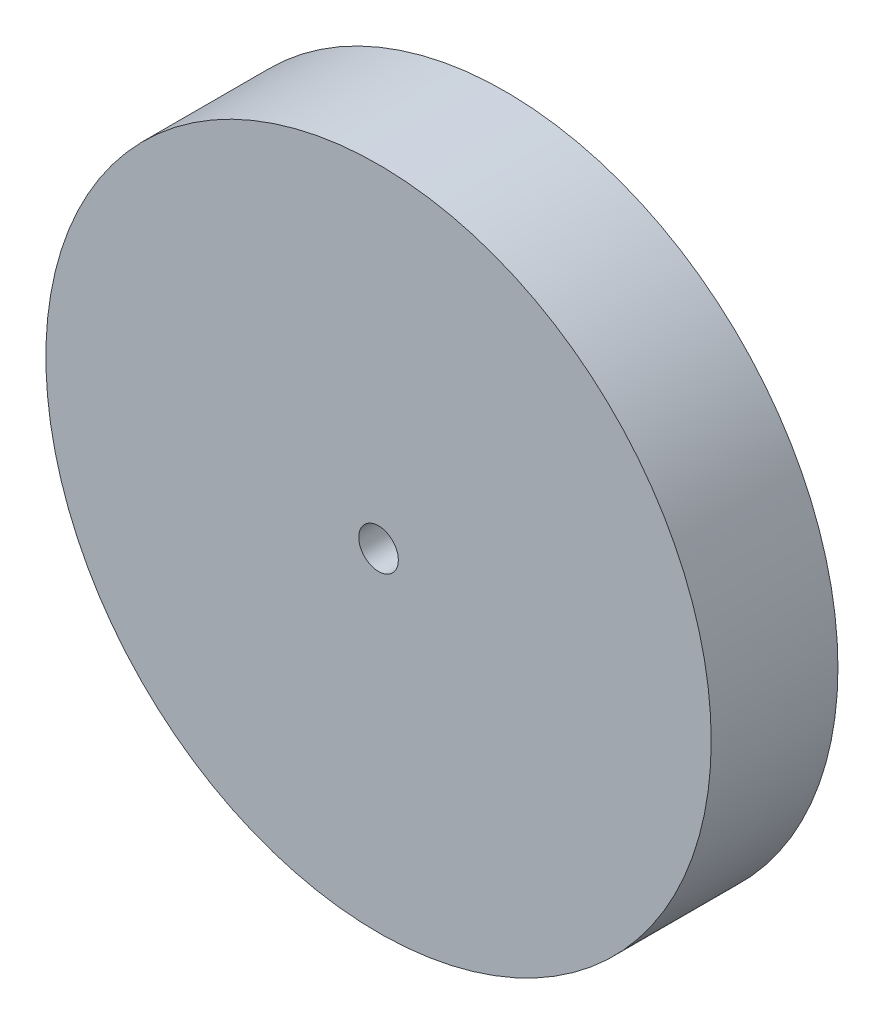
SolidWorks part; units mm, degrees
ref_plane "Front Plane" through (0, 0, 0) normal (0, 0, 1) x (1, 0, 0)
ref_plane "Top Plane" through (0, 0, 0) normal (0, 1, 0) x (1, 0, 0)
ref_plane "Right Plane" through (0, 0, 0) normal (1, 0, 0) x (0, 0, -1)
sketch "Sketch1" plane through (0, 0, 0) normal (0, 0, 1) x (1, 0, 0)
  circle A0 centre (0, 0) radius 21
extrude "Boss-Extrude1" add sketch "Sketch1" along normal blind 8
sketch "Sketch2" plane through (0, 0, 8) normal (0, 0, 1) x (1, 0, 0)
  circle A0 centre (0, 0) radius 1.25
extrude "Cut-Extrude1" cut sketch "Sketch2" against normal blind 8
